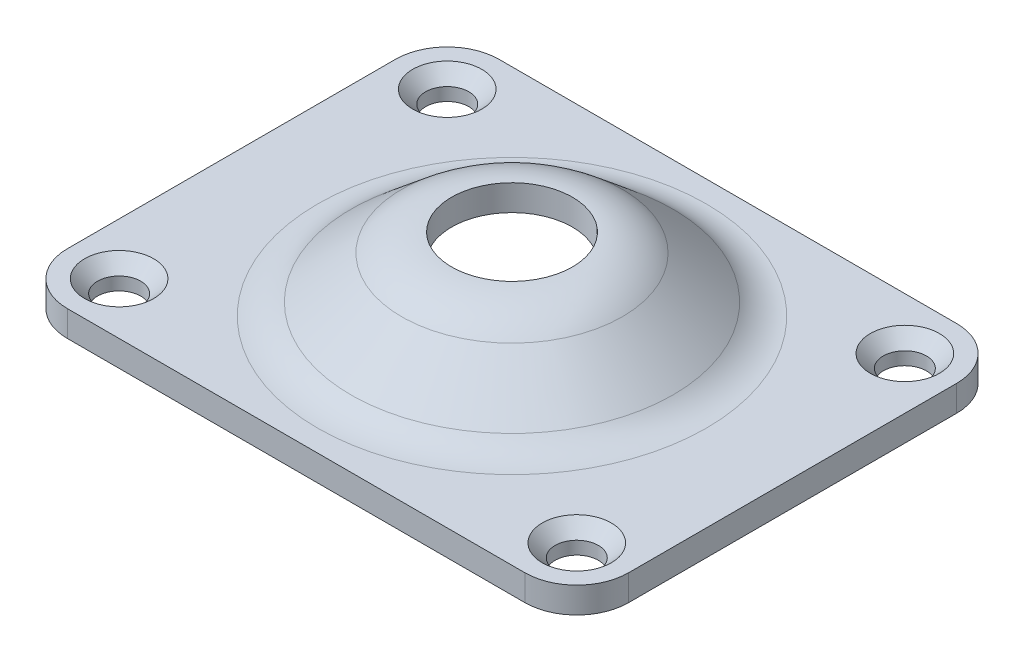
SolidWorks part; units mm, degrees
material "1023 Carbon Steel Sheet (SS)"
ref_plane "Front Plane" through (0, 0, 0) normal (0, 0, 1) x (1, 0, 0)
ref_plane "Top Plane" through (0, 0, 0) normal (0, 1, 0) x (1, 0, 0)
ref_plane "Right Plane" through (0, 0, 0) normal (1, 0, 0) x (0, 0, -1)
sketch "Sketch1" plane through (0, 0, 0) normal (0, 1, 0) x (1, 0, 0)
  line L1 (-26.5, -25) -> (26.5, -25)
  line L2 (-32.5, -19) -> (-32.5, 19)
  line L3 (-26.5, 25) -> (26.5, 25)
  line L4 (32.5, -19) -> (32.5, 19)
  line L5 (-32.5, -25) -> (32.5, 25) construction
  line L6 (-32.5, 25) -> (32.5, -25) construction
  arc A0 (-26.5, -25) -> (-32.5, -19) centre (-26.5, -19) cw
  arc A1 (26.5, -25) -> (32.5, -19) centre (26.5, -19) ccw
  arc A2 (26.5, 25) -> (32.5, 19) centre (26.5, 19) cw
  arc A3 (-32.5, 19) -> (-26.5, 25) centre (-26.5, 19) cw
  circle A4 centre (-26.5, 19) radius 2.5
  circle A5 centre (26.5, 19) radius 2.5
  circle A6 centre (26.5, -19) radius 2.5
  circle A7 centre (-26.5, -19) radius 2.5
  circle A8 centre (0, 0) radius 22.5
  point P0 (0, 0)
  dimension "D3" = 6
  dimension "D4" = 5
  dimension "D5" = 45
  dimension "D1" = 65
  dimension "D2" = 50
extrude "Boss-Extrude1" add sketch "Sketch1" along normal blind 3
sketch "Sketch2" plane through (0, 0, 0) normal (0, 0, 1) x (1, 0, 0)
  line L0 (0, 3) -> (0, 11.4249) construction
  line L1 (-26.5, 3) -> (26.5, 3) construction
  line L2 (0, 3) -> (-22.5, 3) construction
  line L3 (-18.6433, 4.4037) -> (-12.7851, 9.3193)
  line L4 (0, 11.4249) -> (-7, 11.4249) construction
  line L5 (-16.7149, 2.1056) -> (-10.8567, 7.0212)
  line L6 (-7, 11.4249) -> (-7, 8.4249)
  line L7 (-22.5, 3) -> (-22.5, 0)
  arc A0 (-22.5, 3) -> (-18.6433, 4.4037) centre (-22.5, 9) ccw
  arc A1 (-12.7851, 9.3193) -> (-7, 11.4249) centre (-7, 2.4249) cw
  arc A2 (-22.5, 0) -> (-16.7149, 2.1056) centre (-22.5, 9) ccw
  arc A3 (-10.8567, 7.0212) -> (-7, 8.4249) centre (-7, 2.4249) cw
  dimension "D2" = 6
  dimension "D3" = 50
  dimension "D4" = 9
  dimension "D1" = 45
  dimension "D5" = 7
  dimension "D6" = 3
revolve "Revolve1" add sketch "Sketch2" angle 360 about L0
chamfer "Chamfer1" distance 1.5 angle 45 4 edges at (26.5, 3, 21.5) (26.5, 3, -16.5) (-26.5, 3, -16.5) (-26.5, 3, 21.5)
